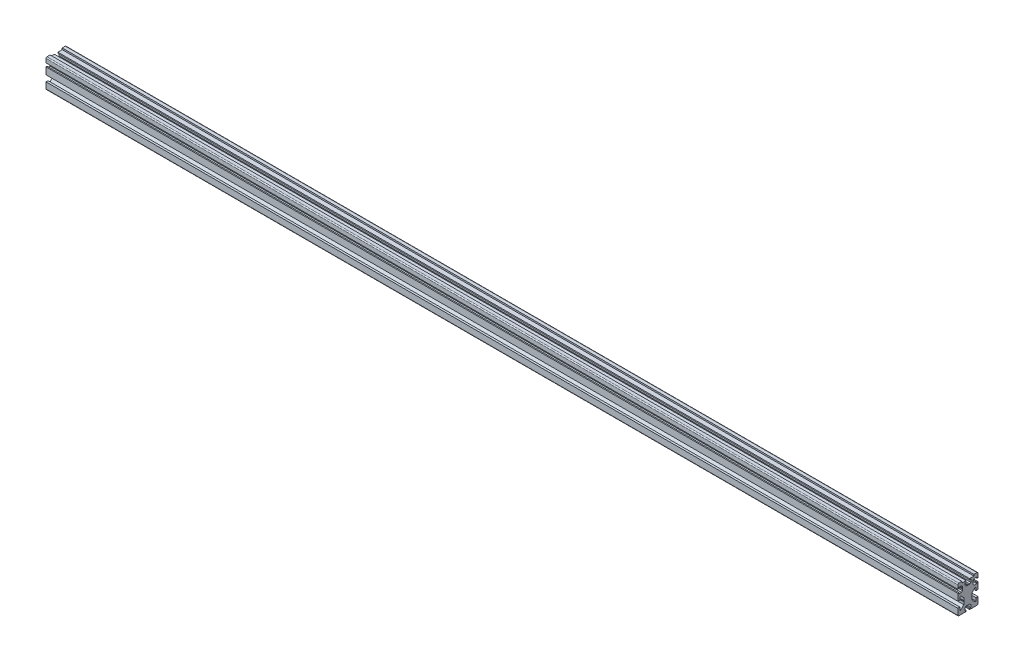
SolidWorks part; units mm, degrees
ref_plane "Front Plane" through (0, 0, 0) normal (0, 0, 1) x (1, 0, 0)
ref_plane "Top Plane" through (0, 0, 0) normal (0, 1, 0) x (1, 0, 0)
ref_plane "Right Plane" through (0, 0, 0) normal (1, 0, 0) x (0, 0, -1)
ref_plane "Plane1" through (24, 0, 0) normal (1, 0, 0) x (0, 0, -1)
ref_plane "Plane2" through (1000, 0, 0) normal (1, 0, 0) x (0, 0, -1)
ref_plane "Plane3" through (925, 0, 0) normal (1, 0, 0) x (0, 0, -1)
ref_plane "Plane4" through (474.5, 0, 0) normal (1, 0, 0) x (0, 0, -1)
sketch "Sketch1" plane through (24, 0, 0) normal (1, 0, 0) x (0, 0, -1)
  line L0 (-5.3, 9.35) -> (-5.3, 8.0196)
  line L1 (-5.3, 8.0196) -> (-5, 7.5)
  line L2 (-5, 7.5) -> (-5.3, 6.9804)
  line L3 (-5.3, 6.9804) -> (-5.3, 5.65)
  line L4 (-5.3, 5.65) -> (-6.3, 4.65)
  line L5 (-6.3, 4.65) -> (-8.9, 4.65)
  line L6 (-8.9, 4.65) -> (-8.9, 5.8)
  line L7 (-8.9, 5.8) -> (-10, 5.8)
  line L8 (-10, 5.8) -> (-10, -1)
  line L9 (-10, -1) -> (-8, -1)
  line L10 (-8, -1) -> (-8, 2)
  line L11 (-8, 2) -> (-7, 2)
  line L12 (-7, 2) -> (-4, -1)
  line L13 (-4, -1) -> (-4, -3.4804)
  line L14 (-4, -3.4804) -> (-3.7, -4)
  line L15 (-3.7, -4) -> (-4, -4.5196)
  line L16 (-4, -4.5196) -> (-4, -7)
  line L17 (-4, -7) -> (-7, -10)
  line L18 (-7, -10) -> (-8, -10)
  line L19 (-8, -10) -> (-8, -7)
  line L20 (-8, -7) -> (-10, -7)
  line L21 (-10, -7) -> (-10, -13)
  line L22 (-9, -14) -> (-1.7, -14)
  line L23 (-1.7, -14) -> (-1.7, -12.9)
  line L24 (-1.7, -12.9) -> (-2.85, -12.9)
  line L25 (-2.85, -12.9) -> (-2.85, -10.3)
  line L26 (-2.85, -10.3) -> (-1.85, -9.3)
  line L27 (-1.85, -9.3) -> (-0.5196, -9.3)
  line L28 (-0.5196, -9.3) -> (0, -9)
  line L29 (0, -9) -> (0.5196, -9.3)
  line L30 (0.5196, -9.3) -> (1.85, -9.3)
  line L31 (1.85, -9.3) -> (2.85, -10.3)
  line L32 (2.85, -10.3) -> (2.85, -12.9)
  line L33 (2.85, -12.9) -> (1.7, -12.9)
  line L34 (1.7, -12.9) -> (1.7, -14)
  line L35 (1.7, -14) -> (9, -14)
  line L36 (10, -13) -> (10, -7)
  line L37 (-5, 7.5) -> (-10, 7.5) construction
  line L38 (-3.7, -4) -> (-10, -4) construction
  line L39 (5, 7.5) -> (10, 7.5) construction
  line L40 (6.3, 10.35) -> (5.3, 9.35)
  line L41 (8.9, 10.35) -> (6.3, 10.35)
  line L42 (8.9, 9.2) -> (8.9, 10.35)
  line L43 (10, 9.2) -> (8.9, 9.2)
  line L44 (8.9, 5.8) -> (10, 5.8)
  line L45 (8.9, 4.65) -> (8.9, 5.8)
  line L46 (6.3, 4.65) -> (8.9, 4.65)
  line L47 (5.3, 5.65) -> (6.3, 4.65)
  line L48 (5.3, 6.9804) -> (5.3, 5.65)
  line L49 (10, -1) -> (10, 5.8)
  line L50 (5, 7.5) -> (5.3, 6.9804)
  line L51 (5.3, 8.0196) -> (5, 7.5)
  line L52 (5.3, 9.35) -> (5.3, 8.0196)
  line L53 (3.7, -4) -> (10, -4) construction
  line L54 (8, -7) -> (10, -7)
  line L55 (8, -10) -> (8, -7)
  line L56 (7, -10) -> (8, -10)
  line L57 (4, -7) -> (7, -10)
  line L58 (4, -4.5196) -> (4, -7)
  line L59 (3.7, -4) -> (4, -4.5196)
  line L60 (4, -3.4804) -> (3.7, -4)
  line L61 (4, -1) -> (4, -3.4804)
  line L62 (7, 2) -> (4, -1)
  line L63 (8, 2) -> (7, 2)
  line L64 (10, 9.2) -> (10, 13)
  line L65 (6, 14) -> (9, 14)
  line L66 (-10, 13) -> (-10, 9.2)
  line L67 (-10, 9.2) -> (-8.9, 9.2)
  line L68 (-8.9, 9.2) -> (-8.9, 10.35)
  line L69 (-8.9, 10.35) -> (-6.3, 10.35)
  line L70 (-6.3, 10.35) -> (-5.3, 9.35)
  line L71 (-1.7, 12.5) -> (-6, 12.5)
  line L72 (-6, 12.5) -> (-6, 14)
  line L73 (-9, 14) -> (-6, 14)
  line L74 (6, 14) -> (6, 12.5)
  line L75 (6, 12.5) -> (1.7, 12.5)
  line L76 (1.7, 12.5) -> (1.7, 11.4)
  line L77 (1.7, 11.4) -> (2.85, 11.4)
  line L78 (2.85, 11.4) -> (2.85, 8.8)
  line L79 (2.85, 8.8) -> (1.85, 7.8)
  line L80 (1.85, 7.8) -> (0.5196, 7.8)
  line L81 (0.5196, 7.8) -> (0, 7.5)
  line L82 (0, 7.5) -> (-0.5196, 7.8)
  line L83 (-0.5196, 7.8) -> (-1.85, 7.8)
  line L84 (-1.85, 7.8) -> (-2.85, 8.8)
  line L85 (-2.85, 8.8) -> (-2.85, 11.4)
  line L86 (-2.85, 11.4) -> (-1.7, 11.4)
  line L87 (-1.7, 11.4) -> (-1.7, 12.5)
  line L88 (10, 0) -> (-10, 0) construction
  line L89 (0, 14) -> (0, -14) construction
  line L90 (11, 0) -> (-11, 0) construction
  line L91 (0, 15.4) -> (0, -15.4) construction
  line L92 (-6, 14) -> (6, 14) construction
  line L93 (-1.7, -14) -> (1.7, -14) construction
  line L94 (8, -1) -> (8, 2)
  line L95 (10, -1) -> (8, -1)
  arc A0 (-10, -13) -> (-9, -14) centre (-9, -13) ccw
  arc A1 (9, -14) -> (10, -13) centre (9, -13) ccw
  arc A2 (10, 13) -> (9, 14) centre (9, 13) ccw
  arc A3 (-9, 14) -> (-10, 13) centre (-9, 13) ccw
  point P46 (0, 12.5)
  dimension "FIX_21" = 2
  dimension "FIX_6" = 1
  dimension "FIX_3" = 14
  dimension "FIX_4" = 28
  dimension "FIX_5" = 20
  dimension "FIX_7" = 12
  dimension "FIX_8" = 1.5
  dimension "FIX_17" = 10
  dimension "FIX_18" = 11.5
  dimension "FIX_19" = 6
  dimension "FIX_20" = 12
  dimension "FIX_22" = 4
extrude "Boss-Extrude1" add sketch "Sketch1" along normal up to surface (901 mm away) up to plane "Plane3"
ref_plane "Plane5" through (0, 0, -10) normal (0, 0, 1) x (1, 0, 0)
sketch "Sketch2" [suppressed] plane through (0, 0, -10) normal (0, 0, 1) x (1, 0, 0)
  line L0 (0, -11) -> (0, 11) construction
  circle A0 centre (85, 7.5) radius 3.55
  dimension "FIX_25" = 7.1
  dimension "FYA" = 85
extrude "Cut-Extrude1" [suppressed] cut sketch "Sketch2" along normal up to surface (1.1 mm away)
sketch "Sketch3" [suppressed] plane through (0, 0, -10) normal (0, 0, 1) x (1, 0, 0)
  circle A0 centre (85, -4) radius 6.05
  dimension "FIX_26" = 12.1
extrude "Cut-Extrude2" [suppressed] cut sketch "Sketch3" along normal up to surface (2 mm away)
sketch "Sketch4" [suppressed] plane through (0, 0, -10) normal (0, 0, 1) x (1, 0, 0)
  line L0 (0, -11) -> (0, 11) construction
  circle A0 centre (820, 7.5) radius 3.55
  dimension "FIX_27" = 7.1
  dimension "FYB" = 820
extrude "Cut-Extrude3" [suppressed] cut sketch "Sketch4" along normal up to surface (1.1 mm away)
sketch "Sketch5" [suppressed] plane through (0, 0, -10) normal (0, 0, 1) x (1, 0, 0)
  circle A0 centre (820, -4) radius 6.05
  dimension "FIX_28" = 12.1
extrude "Cut-Extrude4" [suppressed] cut sketch "Sketch5" along normal up to surface (2 mm away)
